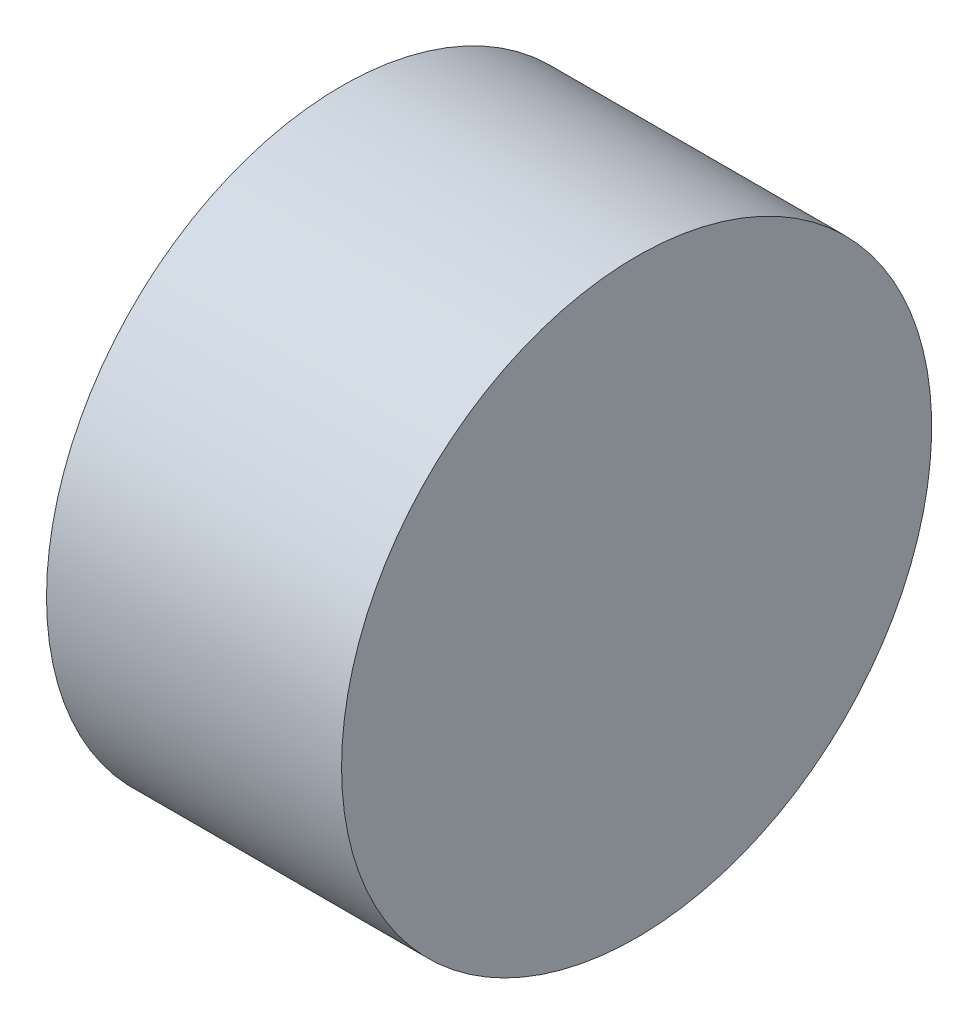
SolidWorks part; units mm, degrees
material "Custom Plastic"
ref_plane "Front Plane" through (0, 0, 0) normal (0, 0, 1) x (1, 0, 0)
ref_plane "Top Plane" through (0, 0, 0) normal (0, 1, 0) x (1, 0, 0)
ref_plane "Right Plane" through (0, 0, 0) normal (1, 0, 0) x (0, 0, -1)
sketch "Sketch2" plane through (0, 0, 0) normal (1, 0, 0) x (0, 0, -1)
  circle A0 centre (0, 0) radius 76.2
  dimension "D1" = 152.4
extrude "Boss-Extrude1" add sketch "Sketch2" along normal mid plane 76.2
sketch "Sketch5" plane through (-38.1, 0, 0) normal (-1, 0, 0) x (0, 0, 1)
  line L0 (0, -63.5) -> (0, -76.2) construction
  circle A0 centre (0, 0) radius 63.5
  circle A1 centre (0, 0) radius 76.2 construction
  dimension "D1" = 12.7
extrude "Cut-Extrude2" cut sketch "Sketch5" against normal blind 51.6
sketch "Sketch6" plane through (0, 0, 0) normal (0, 1, 0) x (1, 0, 0)
  line L0 (0, 0) -> (13.5, 0) construction
  line L1 (13.5, 0) -> (13.5, 25)
  line L2 (13.5, 0) -> (13.5, -25)
  circle A0 centre (0, 0) radius 3.75
  arc A1 (13.5, -25) -> (13.5, 25) centre (13.5, 0) cw
  point P3 (13.5, 0)
  point P4 (0, 0)
  dimension "D4" = 7.5
  dimension "D1" = 13.5
  dimension "D3" = 50
extrude "Boss-Extrude4" add sketch "Sketch6" along normal mid plane 25.4 separate body
equation "\"WheelInnerDia\"=0.1524"
equation "\"D1@Sketch2\"=\"WheelInnerDia\""
equation "\"WheelThickness\"=0.0762"
equation "\"D1@Boss-Extrude1\"=\"WheelThickness\""
